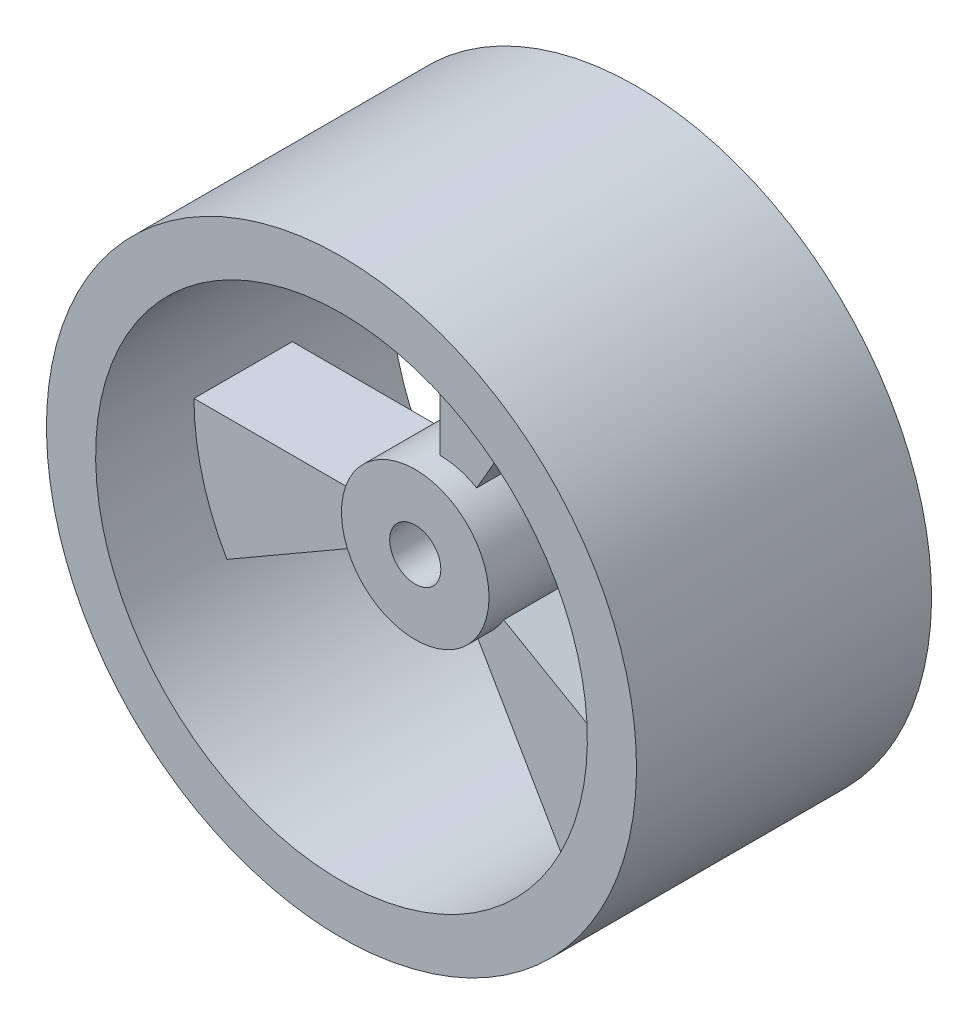
SolidWorks part; units mm, degrees
ref_plane "Alzado" through (0, 0, 0) normal (0, 0, 1) x (1, 0, 0)
ref_plane "Planta" through (0, 0, 0) normal (0, 1, 0) x (1, 0, 0)
ref_plane "Vista lateral" through (0, 0, 0) normal (1, 0, 0) x (0, 0, -1)
sketch "Sketch5" plane through (0, 0, 0) normal (1, 0, 0) x (0, 0, -1)
  line L0 (-5, 7.5) -> (-5, 25)
  line L1 (-5, 25) -> (-15, 25)
  line L2 (-15, 25) -> (-15, 30)
  line L3 (-15, 30) -> (15, 30)
  line L4 (15, 30) -> (15, 25)
  line L5 (15, 25) -> (5, 25)
  line L6 (5, 25) -> (5, 7.5)
  line L7 (-5, 7.5) -> (-7.5, 7.5)
  line L8 (-7.5, 7.5) -> (-7.5, 0)
  line L9 (5, 7.5) -> (7.5, 7.5)
  line L10 (7.5, 7.5) -> (7.5, 0)
  line L11 (11.452, 0) -> (-11.452, 0) construction
  line L12 (-7.5, 0) -> (7.5, 0)
  point P2 (0, 0)
  point P10 (0, 30)
  dimension "D1" = 30
  dimension "D2" = 5
  dimension "D3" = 10
  dimension "D4" = 30
  dimension "D5" = 7.5
  dimension "D6" = 15
revolve "Revolve2" add sketch "Sketch5" angle 360 about L11
sketch "Sketch7" plane through (0, 0, 5) normal (0, 0, 1) x (1, 0, 0)
  line L0 (0, 7.5) -> (0, 25)
  line L1 (-7.5, 0) -> (-25, 0)
  circle A1 centre (0, 0) radius 7.5 construction
  arc A2 (0, 7.5) -> (-7.5, 0) centre (0, 0) ccw
  circle A3 centre (0, 0) radius 25 construction
  circle A4 centre (0, 0) radius 25 construction
  arc A5 (0, 25) -> (-25, 0) centre (0, 0) ccw
  dimension "D1" = 25
extrude "Cut-Extrude1" cut sketch "Sketch7" against normal through all
pattern_circular "CirPattern2" count 3 over 360 about axis through (0, 0, 0) along (0, 0, 1) of "Cut-Extrude1"
sketch "Sketch8" plane through (0, 0, -7.5) normal (0, 0, -1) x (-1, 0, 0)
  circle A0 centre (0, 0) radius 2.6
  dimension "D1" = 5.2
extrude "Cut-Extrude2" cut sketch "Sketch8" against normal through all
